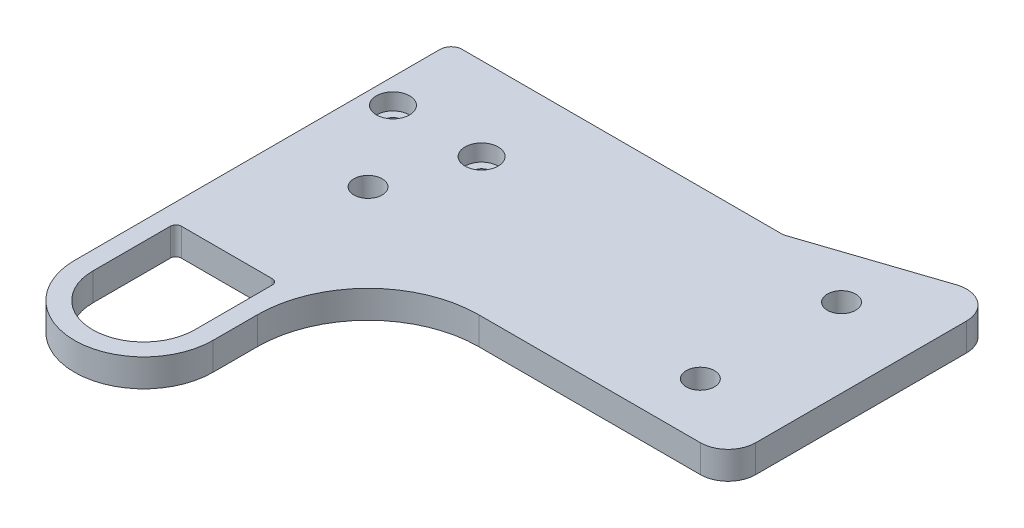
SolidWorks part; units mm, degrees
ref_plane "正面" through (0, 0, 0) normal (0, 0, 1) x (1, 0, 0)
ref_plane "平面" through (0, 0, 0) normal (0, 1, 0) x (1, 0, 0)
ref_plane "右側面" through (0, 0, 0) normal (1, 0, 0) x (0, 0, -1)
sketch "ｽｹｯﾁ1" plane through (0, 0, 0) normal (0, 1, 0) x (1, 0, 0)
  line L0 (0, 0) -> (180, 0) construction
  line L1 (180, 0) -> (180, 60) construction
  line L2 (0, 0) -> (0, -48)
  line L3 (0, -48) -> (25, -48) construction
  line L4 (25, -48) -> (25, -20)
  line L5 (180, 60) -> (0, 0) construction
  line L6 (0, 0) -> (90, 30)
  line L7 (90, 30) -> (90, -20)
  line L8 (90, -20) -> (25, -20)
  line L9 (0, -10) -> (90, -10) construction
  line L10 (90, 19.4591) -> (0, -10.5409) construction
  arc A0 (0, -48) -> (25, -48) centre (12.5, -48) ccw
  circle A1 centre (75.7698, 14.7157) radius 2.55
  circle A2 centre (75, -10) radius 2.55
  circle A3 centre (15, -10) radius 2.55
  circle A4 centre (12.5, -48) radius 7.5
  dimension "D5" = 25
  dimension "D9" = 15
  dimension "D12" = 5.1
  dimension "D13" = 15
  dimension "D1" = 60
  dimension "D2" = 180
  dimension "D3" = 20
  dimension "D4" = 90
  dimension "D6" = 28
  dimension "D7" = 10
  dimension "D8" = 10
  dimension "D10" = 15
  dimension "D11" = 15
extrude "ﾎﾞｽ - 押し出し1" add sketch "ｽｹｯﾁ1" along normal blind 5
fillet "ﾌｨﾚｯﾄ1" radius 20 1 edges at (25, 2.5, 20)
fillet "ﾌｨﾚｯﾄ2" radius 5 2 edges at (90, 2.5, -30) (90, 2.5, 20)
sketch "ｽｹｯﾁ2" plane through (0, 5, 0) normal (0, 1, 0) x (1, 0, 0)
  line L0 (3.3, -48) -> (3.3, -34)
  line L1 (4.3, -33) -> (20.7, -33)
  line L2 (21.7, -34) -> (21.7, -48)
  arc A0 (3.3, -48) -> (21.7, -48) centre (12.5, -48) ccw
  arc A1 (3.3, -34) -> (4.3, -33) centre (4.3, -34) cw
  arc A2 (20.7, -33) -> (21.7, -34) centre (20.7, -34) cw
  point P10 (21.7, -33)
  dimension "D1" = 9.2
  dimension "D3" = 1
  dimension "D2" = 15
extrude "ｶｯﾄ - 押し出し1" cut sketch "ｽｹｯﾁ2" against normal through all
sketch "ｽｹｯﾁ4" plane through (0, 5, 0) normal (0, 1, 0) x (1, 0, 0)
  line L0 (0, 0) -> (0, 20)
  line L1 (0, 20) -> (60, 20)
  line L2 (83.4189, 27.8063) -> (0, 0) construction
  line L3 (60, 20) -> (0, 0)
  dimension "D1" = 20
extrude "ﾎﾞｽ - 押し出し2" add sketch "ｽｹｯﾁ4" against normal up to surface (5 mm away) up to face at (12.5, 0, 39.7976)
sketch "ｽｹｯﾁ3" plane through (0, 5, 0) normal (0, 1, 0) x (1, 0, 0)
  line L0 (12.5, -60.5) -> (12.5, 5) construction
  line L1 (12.5, 5) -> (20.5, 5) construction
  line L2 (20.7, -33) -> (4.3, -33) construction
  arc A0 (0, -48) -> (25, -48) centre (12.5, -48) ccw construction
  circle A1 centre (20.5, 5) radius 1.55
  circle A2 centre (4.5, 5) radius 1.55
  dimension "D1" = 3.1
  dimension "D2" = 38
  dimension "D3" = 8
extrude "ｶｯﾄ - 押し出し2" cut sketch "ｽｹｯﾁ3" against normal through all
fillet "ﾌｨﾚｯﾄ3" radius 2 2 edges at (60, 2.5, -20) (0, 2.5, -20)
sketch "ｽｹｯﾁ5" plane through (0, 5, 0) normal (0, -1, 0) x (1, 0, 0)
  circle A0 centre (4.5, -5) radius 3
  circle A1 centre (20.5, -5) radius 3
  dimension "D1" = 6
extrude "ｶｯﾄ - 押し出し3" cut sketch "ｽｹｯﾁ5" along normal blind 3
